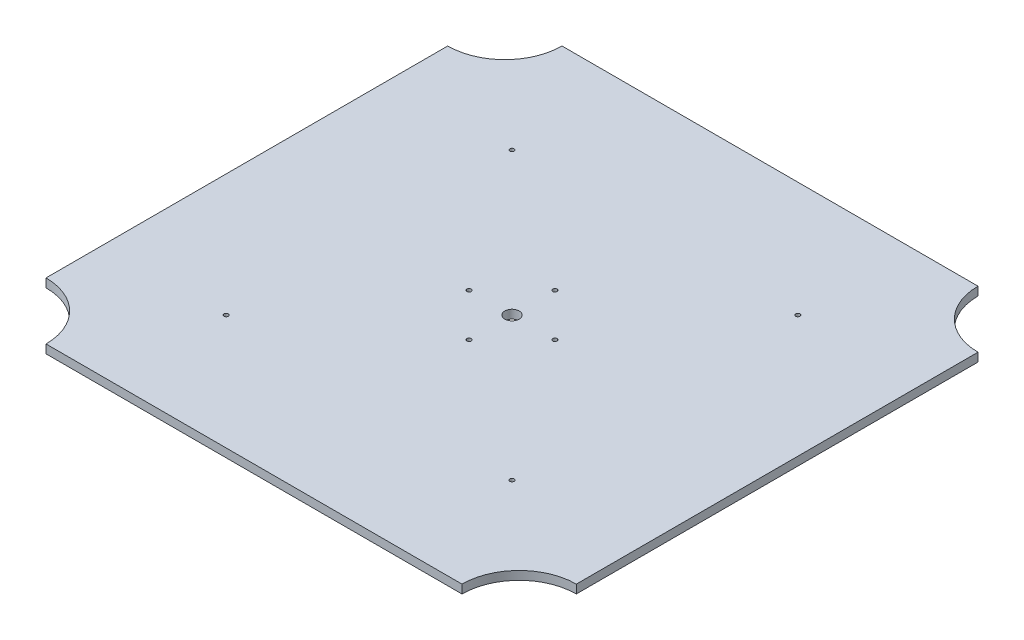
SolidWorks part; units mm, degrees
material "有机玻璃 (TM) GS 丙烯酸铸钣"
ref_plane "前视基准面" through (0, 0, 0) normal (0, 0, 1) x (1, 0, 0)
ref_plane "上视基准面" through (0, 0, 0) normal (0, 1, 0) x (1, 0, 0)
ref_plane "右视基准面" through (0, 0, 0) normal (1, 0, 0) x (0, 0, -1)
other "Configuration Table"
sketch "草图1" plane through (0, 0, 0) normal (0, 1, 0) x (1, 0, 0)
  line L0 (0, 180.5) -> (0, -180.5) construction
  line L1 (-145.5, 180.5) -> (145.5, 180.5)
  line L2 (-185.5, 140.5) -> (-185.5, -140.5)
  line L3 (-145.5, -180.5) -> (145.5, -180.5)
  line L4 (185.5, 140.5) -> (185.5, -140.5)
  line L5 (-185.5, 0) -> (185.5, 0) construction
  line L6 (-100, 100) -> (100, 100) construction
  line L7 (100, 100) -> (100, -100) construction
  line L8 (100, -100) -> (-100, -100) construction
  line L9 (-100, -100) -> (-100, 100) construction
  arc A0 (-185.5, 140.5) -> (-145.5, 180.5) centre (-185.5, 180.5) ccw
  arc A1 (145.5, 180.5) -> (185.5, 140.5) centre (185.5, 180.5) ccw
  arc A2 (185.5, -140.5) -> (145.5, -180.5) centre (185.5, -180.5) ccw
  arc A3 (-145.5, -180.5) -> (-185.5, -140.5) centre (-185.5, -180.5) ccw
  circle A4 centre (0, 0) radius 5
  circle A5 centre (0, 30) radius 1.5
  circle A6 centre (30, 0) radius 1.5
  circle A7 centre (0, -30) radius 1.5
  circle A8 centre (-30, 0) radius 1.5
  circle A9 centre (-100, 100) radius 1.5
  circle A10 centre (100, 100) radius 1.5
  circle A11 centre (100, -100) radius 1.5
  circle A12 centre (-100, -100) radius 1.5
  point P0 (0, 0)
  point P31 (0, 0)
  dimension "D1" = 40
  dimension "D4" = 10
  dimension "D5" = 3
  dimension "D12" = 3
  dimension "D2" = 371
  dimension "D3" = 361
  dimension "D6" = 30
  dimension "D8" = 200
  dimension "D9" = 200
  dimension "D10" = 100
  dimension "D11" = 100
  dimension "D7" = 4
extrude "底图" add sketch "草图1" along normal blind 6
